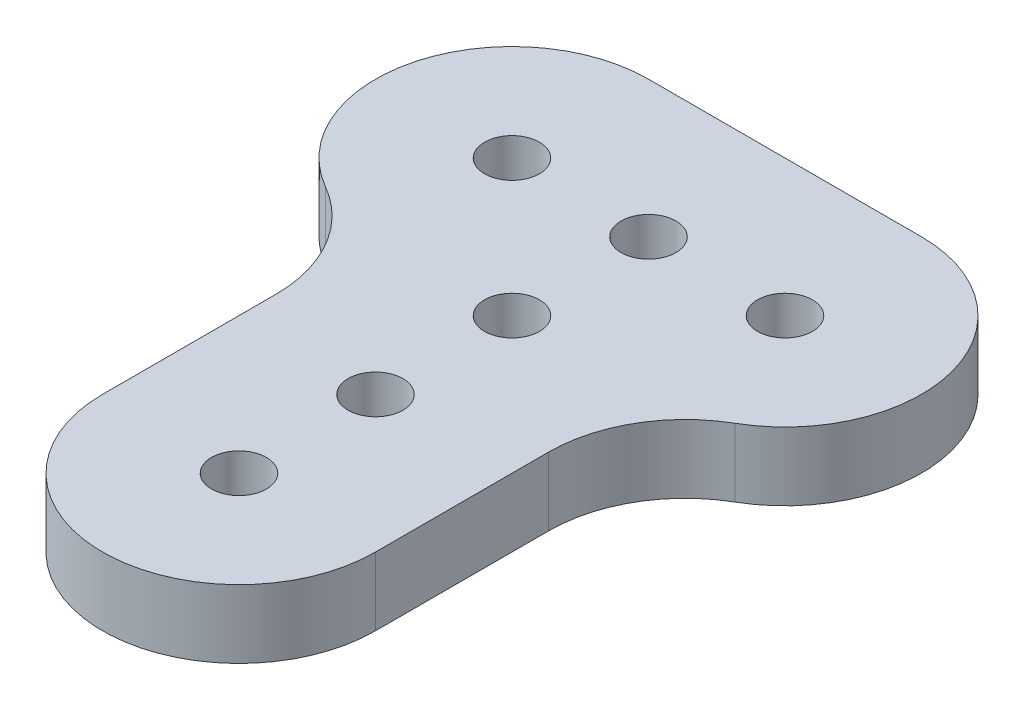
SolidWorks part; units mm, degrees
material "Birch Plywood"
ref_plane "Front Plane" through (0, 0, 0) normal (0, 0, 1) x (1, 0, 0)
ref_plane "Top Plane" through (0, 0, 0) normal (0, 1, 0) x (1, 0, 0)
ref_plane "Right Plane" through (0, 0, 0) normal (1, 0, 0) x (0, 0, -1)
sketch "Sketch1" plane through (0, 0, 0) normal (0, 1, 0) x (1, 0, 0)
  line L0 (0, 0) -> (12.7, 0) construction
  line L1 (25.4, 0) -> (25.4, -12.7) construction
  line L2 (0, 0) -> (50.8, 0) construction
  line L3 (0, 12.7) -> (50.8, 12.7)
  line L4 (0, -12.7) -> (50.8, -12.7)
  line L5 (25.4, -38.1) -> (25.4, 0) construction
  line L6 (12.7, -38.1) -> (12.7, 0)
  line L7 (38.1, -38.1) -> (38.1, 0)
  line L8 (12.7, 0) -> (38.1, 0) construction
  line L9 (12.7, 12.7) -> (38.1, 12.7)
  line L10 (12.7, -12.7) -> (38.1, -12.7)
  circle A0 centre (0, 0) radius 2.5527
  circle A1 centre (12.7, 0) radius 2.5527
  circle A2 centre (25.4, 0) radius 2.5527
  circle A3 centre (38.1, 0) radius 2.5527
  circle A4 centre (50.8, 0) radius 2.5527
  circle A5 centre (25.4, -12.7) radius 2.5527
  circle A6 centre (25.4, -25.4) radius 2.5527
  circle A7 centre (25.4, -38.1) radius 2.5527
  arc A8 (12.7, 12.7) -> (12.7, -12.7) centre (12.7, 0) ccw
  arc A9 (0, 12.7) -> (0, -12.7) centre (0, 0) ccw
  arc A10 (50.8, -12.7) -> (50.8, 12.7) centre (50.8, 0) ccw
  arc A11 (12.7, -38.1) -> (38.1, -38.1) centre (25.4, -38.1) ccw
  arc A12 (38.1, 0) -> (12.7, 0) centre (25.4, 0) ccw
  arc A13 (38.1, -12.7) -> (38.1, 12.7) centre (38.1, 0) ccw
  point P3 (25.4, 0)
  point P21 (25.4, 0)
  point P27 (25.4, -19.05)
  dimension "D1" = 5.1054
  dimension "D6" = 12.7
  dimension "D3" = 12.7
  dimension "D5" = 12.7
  dimension "D2" = 5
  dimension "D4" = 4
extrude "Boss-Extrude1" add sketch "Sketch1" along normal mid plane 6.35
fillet "Fillet1" radius 12.7 2 edges at (12.7, 0, 12.7) (38.1, 0, 12.7)
